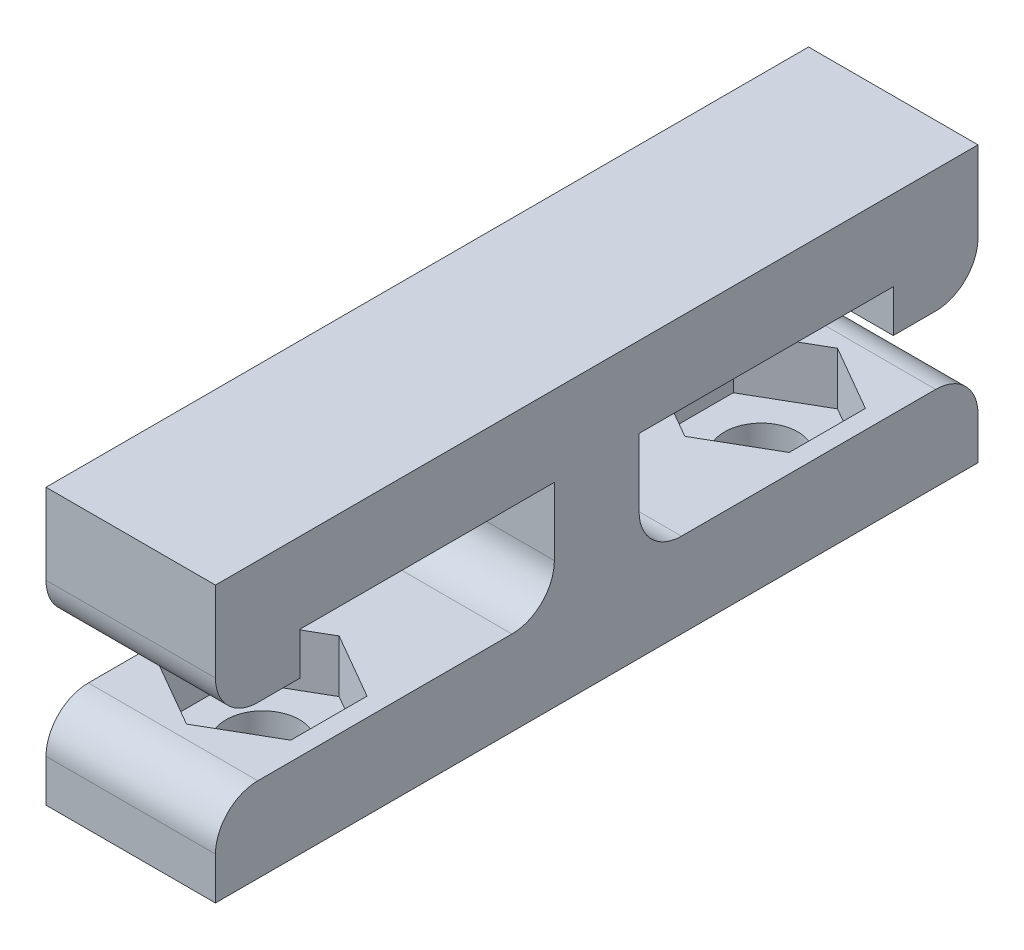
SolidWorks part; units mm, degrees
ref_plane "Front Plane" through (0, 0, 0) normal (0, 0, 1) x (1, 0, 0)
ref_plane "Top Plane" through (0, 0, 0) normal (0, 1, 0) x (1, 0, 0)
ref_plane "Right Plane" through (0, 0, 0) normal (1, 0, 0) x (0, 0, -1)
sketch "Sketch1" plane through (0, 0, 0) normal (0, 1, 0) x (1, 0, 0)
  line L0 (5, 45) -> (5, 0) construction
  line L1 (0, 0) -> (10, 0)
  line L2 (0, 0) -> (0, 45)
  line L3 (0, 45) -> (10, 45)
  line L4 (10, 0) -> (10, 45)
  line L5 (0, 22.5) -> (10, 22.5) construction
  circle A0 centre (5, 37.205) radius 2.16
  circle A1 centre (5, 7.795) radius 2.16
  dimension "D3" = 29.41
  dimension "D4" = 14.705
  dimension "D5" = 4.32
  dimension "D6" = 4.32
  dimension "D1" = 10
  dimension "D2" = 45
extrude "Boss-Extrude1" add sketch "Sketch1" along normal blind 5
sketch "Sketch2" plane through (0, 5, 0) normal (0, 1, 0) x (1, 0, 0)
  line L1 (5, 32.7017) -> (8.9, 34.9533)
  line L2 (8.9, 34.9533) -> (8.9, 39.4567)
  line L3 (8.9, 39.4567) -> (5, 41.7083)
  line L4 (5, 41.7083) -> (1.1, 39.4567)
  line L5 (1.1, 39.4567) -> (1.1, 34.9533)
  line L6 (1.1, 34.9533) -> (5, 32.7017)
  line L7 (5, 12.2983) -> (1.1, 10.0467)
  line L8 (1.1, 10.0467) -> (1.1, 5.5433)
  line L9 (1.1, 5.5433) -> (5, 3.2917)
  line L10 (5, 3.2917) -> (8.9, 5.5433)
  line L11 (8.9, 5.5433) -> (8.9, 10.0467)
  line L12 (8.9, 10.0467) -> (5, 12.2983)
  circle A0 centre (5, 37.205) radius 3.9 construction
  circle A1 centre (5, 7.795) radius 3.9 construction
  dimension "D1" = 7.8
  dimension "D2" = 7.8
extrude "Cut-Extrude1" cut sketch "Sketch2" against normal blind 3.1
sketch "Sketch3" plane through (0, 0, 0) normal (-1, 0, 0) x (0, 0, 1)
  line L0 (-22.5, 5) -> (-22.5, 0) construction
  line L1 (-45, 5) -> (0, 5) construction
  line L2 (-45, 0) -> (0, 0) construction
  line L3 (-25, 5) -> (-25, 11.5)
  line L4 (-25, 11.5) -> (-40, 11.5)
  line L5 (-40, 11.5) -> (-40, 9)
  line L6 (-40, 9) -> (-45, 9)
  line L7 (-45, 9) -> (-45, 16.25)
  line L8 (-45, 16.25) -> (0, 16.25)
  line L9 (-20, 5) -> (-20, 11.5)
  line L10 (0, 9) -> (0, 16.25)
  line L11 (-5, 9) -> (0, 9)
  line L12 (-5, 11.5) -> (-5, 9)
  line L13 (-20, 11.5) -> (-5, 11.5)
  line L14 (-25, 5) -> (-20, 5)
  point P16 (-22.5, 16.25)
  dimension "D1" = 6.5
  dimension "D2" = 15
  dimension "D3" = 5
  dimension "D4" = 7.25
  dimension "D5" = 5
  dimension "D6" = 2.5
extrude "Boss-Extrude2" add sketch "Sketch3" against normal through all
fillet "Fillet1" radius 2.5 6 edges at (5, 5, -45) (5, 5, 0) (5, 9, 0) (5, 9, -45) (5, 5, -20) (5, 5, -25)
